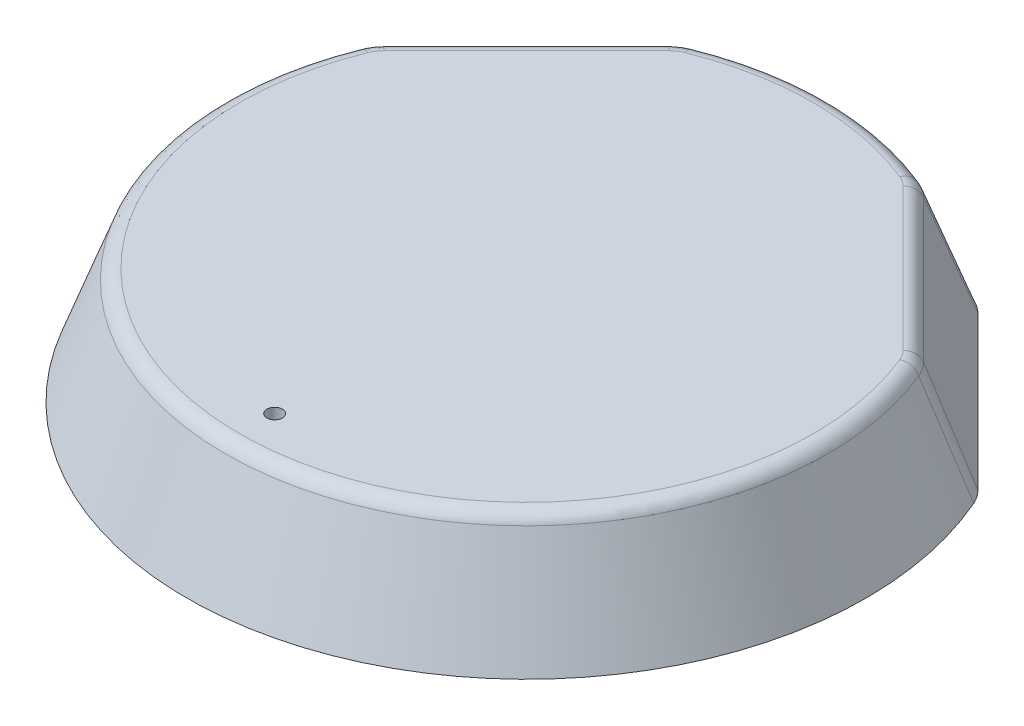
SolidWorks part; units mm, degrees
ref_plane "前视基准面" through (0, 0, 0) normal (0, 0, 1) x (1, 0, 0)
ref_plane "上视基准面" through (0, 0, 0) normal (0, 1, 0) x (1, 0, 0)
ref_plane "右视基准面" through (0, 0, 0) normal (1, 0, 0) x (0, 0, -1)
sketch "草图1" plane through (0, 0, 0) normal (0, 1, 0) x (1, 0, 0)
  line L0 (0, 0) -> (-35.3794, 75.8714) construction
  line L1 (0, 0) -> (0, 71.032) construction
  line L2 (0, 0) -> (-74.5062, 34.7428) construction
  line L3 (-18.5952, 39.8775) -> (-39.8775, 18.5952)
  line L4 (18.5952, 39.8775) -> (39.8775, 18.5952)
  arc A0 (-39.8775, 18.5952) -> (39.8775, 18.5952) centre (0, 0) ccw
  arc A1 (18.5952, 39.8775) -> (-18.5952, 39.8775) centre (0, 0) ccw
  dimension "D1" = 88
  dimension "D2" = 25
  dimension "D3" = 40
extrude "凸台-拉伸1" add sketch "草图1" along normal blind 15
draft "拔模2" type of draft neutral plane draft angle 20 faces to draft 4 face at (29.2364, 7.5, -29.2364) face at (0, 7.5, 12.7024) face at (-29.2364, 7.5, -29.2364) face at (0, 7.5, -41.9388) neutral plane through (0, 0, 0) neutral plane normal (0, -1, 0) reverse direction yes parameters "D1"=20
fillet "圆角1" radius 6 4 edges
fillet "圆角2" radius 2 8 edges at (-35.6243, 15, -14.678) (-25.3759, 15, -25.3759) (-15.9466, 15, -34.7874) (0, 15, -38.5404) (14.678, 15, -35.6243) (25.3759, 15, -25.3759) (34.7874, 15, -15.9466) (0, 15, 38.5404)
sketch "草图2" plane through (0, 0, 0) normal (0, 1, 0) x (1, 0, 0)
  circle A0 centre (0, -32.6148) radius 1
  dimension "D1" = 2
extrude "切除-拉伸1" cut sketch "草图2" along normal through all from offset 6
